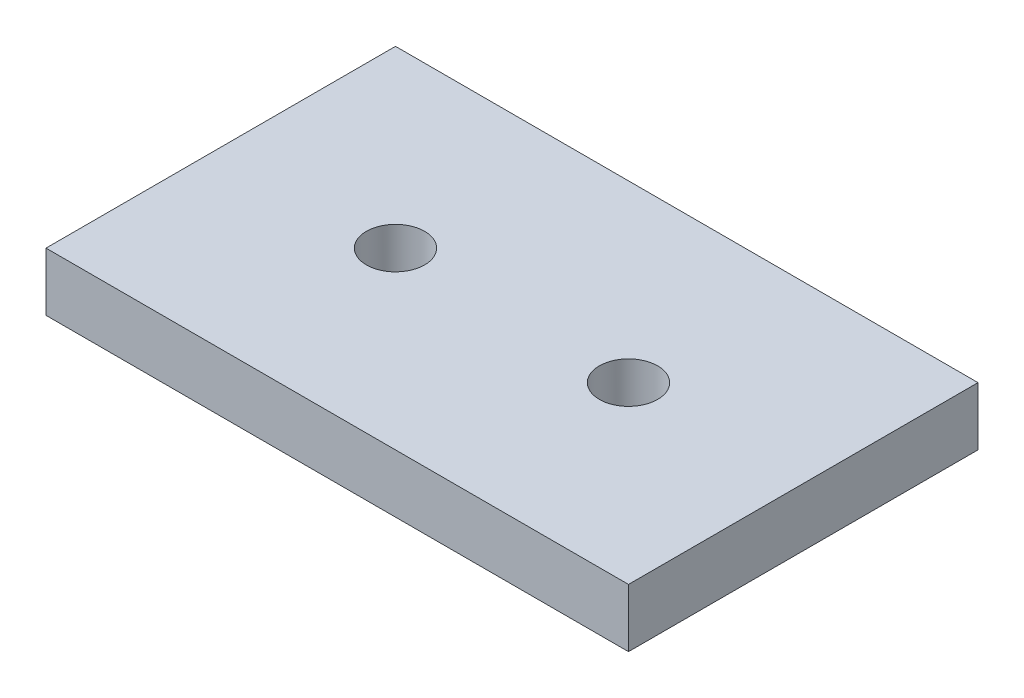
SolidWorks part; units mm, degrees
ref_plane "前视基准面" through (0, 0, 0) normal (0, 0, 1) x (1, 0, 0)
ref_plane "上视基准面" through (0, 0, 0) normal (0, 1, 0) x (1, 0, 0)
ref_plane "右视基准面" through (0, 0, 0) normal (1, 0, 0) x (0, 0, -1)
other "Configuration Table"
sketch "草图1" plane through (0, 0, 0) normal (0, 1, 0) x (1, 0, 0)
  line L1 (-50, -30) -> (50, -30)
  line L2 (-50, -30) -> (-50, 30)
  line L3 (-50, 30) -> (50, 30)
  line L4 (50, -30) -> (50, 30)
  line L5 (-50, -30) -> (50, 30) construction
  line L6 (-50, 30) -> (50, -30) construction
  point P0 (0, 0)
extrude "凸台-拉伸1" add sketch "草图1" along normal blind 10
sketch "草图2" plane through (0, 0, 0) normal (0, 1, 0) x (1, 0, 0)
  circle A0 centre (-20, 0) radius 5
extrude "切除-拉伸1" cut sketch "草图2" along normal blind 20
sketch "草图3" plane through (0, 0, 0) normal (0, 1, 0) x (1, 0, 0)
  circle A0 centre (20, 0) radius 5
extrude "切除-拉伸2" cut sketch "草图3" along normal blind 20
sketch "草图4" plane through (0, 0, 0) normal (0, 1, 0) x (1, 0, 0)
  line L0 (-10, -20) -> (10, -20)
